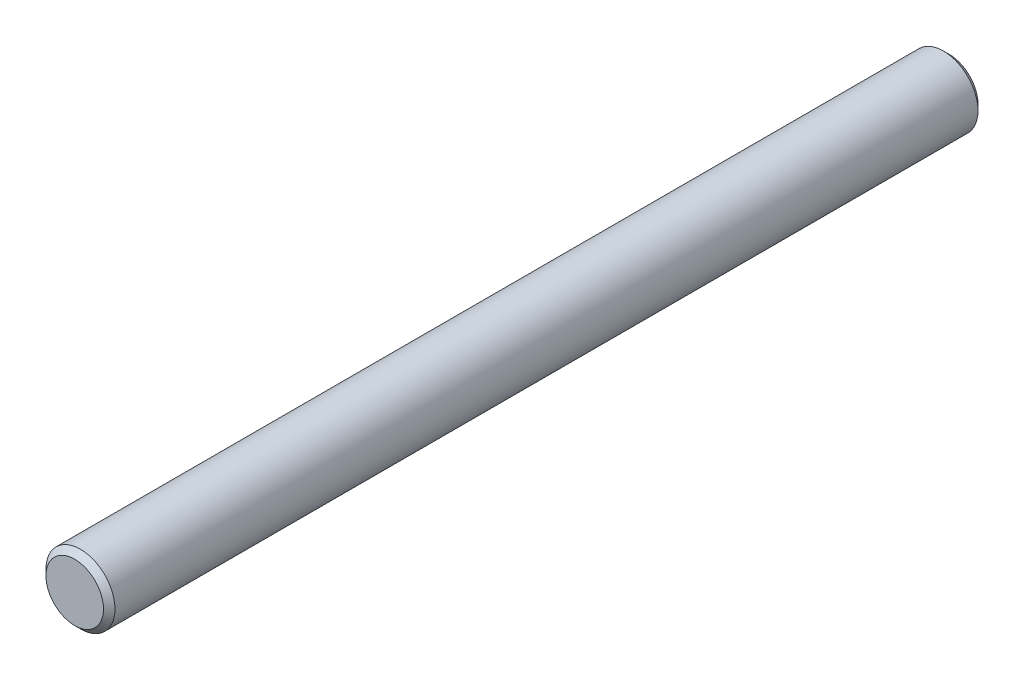
SolidWorks part; units mm, degrees
ref_plane "Piano frontale" through (0, 0, 0) normal (0, 0, 1) x (1, 0, 0)
ref_plane "Piano superiore" through (0, 0, 0) normal (0, 1, 0) x (1, 0, 0)
ref_plane "Piano destro" through (0, 0, 0) normal (1, 0, 0) x (0, 0, -1)
sketch "Schizzo1" plane through (0, 0, 0) normal (0, 0, 1) x (1, 0, 0)
  circle A0 centre (0, 0) radius 1.5
  dimension "D1" = 3
extrude "Estrusione-Estrusione1" add sketch "Schizzo1" along normal blind 38
chamfer "Smusso1" distance 0.25 angle 45 2 edges at (1.5, 0, 38) (1.5, 0, 0)
